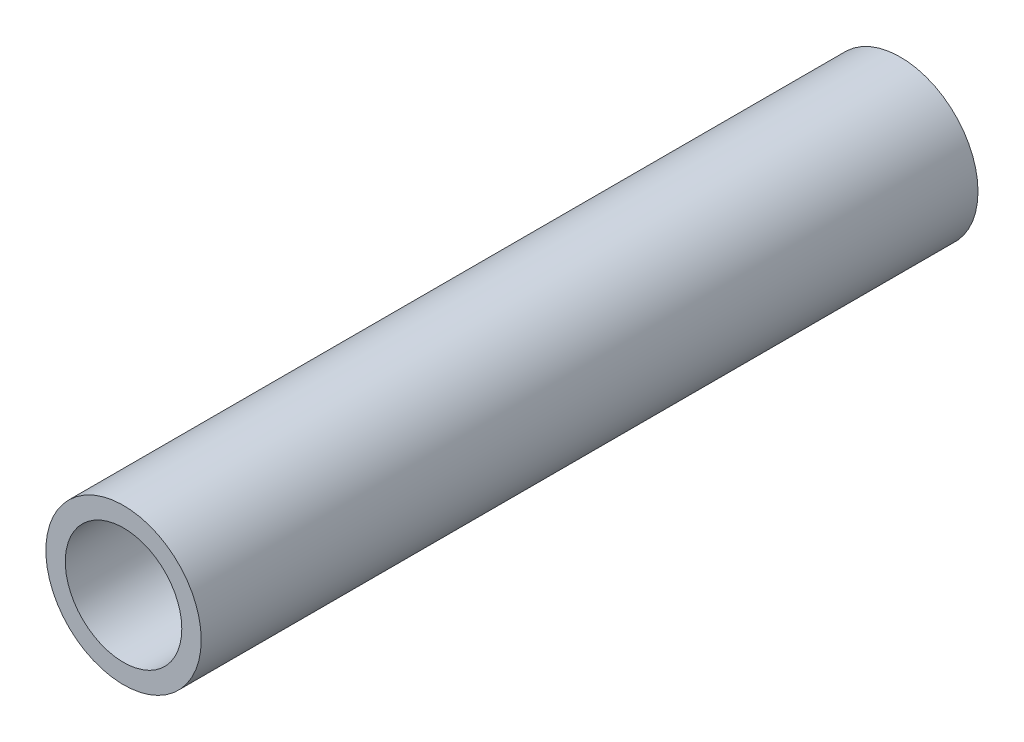
SolidWorks part; units mm, degrees
material "PVC 0.007 Plasticized"
ref_plane "Front Plane" through (0, 0, 0) normal (0, 0, 1) x (1, 0, 0)
ref_plane "Top Plane" through (0, 0, 0) normal (0, 1, 0) x (1, 0, 0)
ref_plane "Right Plane" through (0, 0, 0) normal (1, 0, 0) x (0, 0, -1)
sketch "ProfileS" plane through (0, 0, 0) normal (0, 0, 1) x (1, 0, 0)
  circle A0 centre (0, 0) radius 2
  circle A1 centre (0, 0) radius 1.5
  dimension "OuterDiameter" = 4
  dimension "RefInnerDiameter" = 3
  dimension "OuterWireThickness" = 0.5
extrude "Profile" add sketch "ProfileS" along normal mid plane 20
